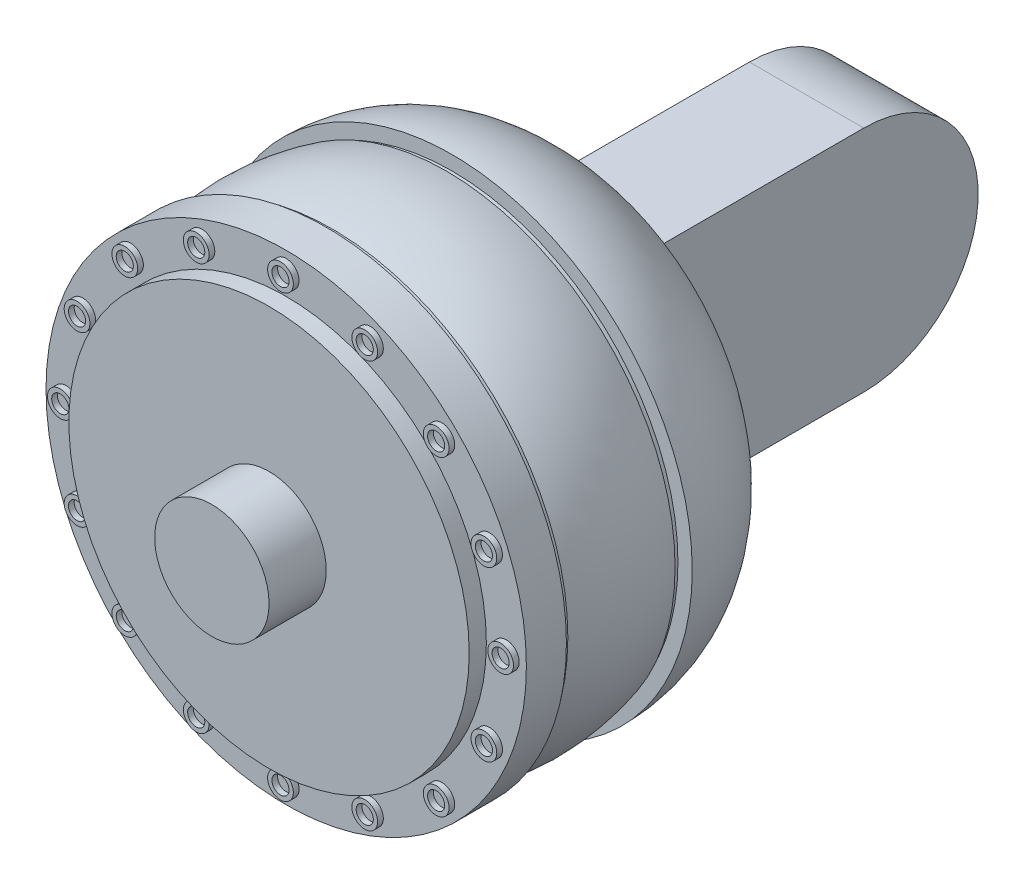
SolidWorks part; units mm, degrees
ref_plane "Front Plane" through (0, 0, 0) normal (0, 0, 1) x (1, 0, 0)
ref_plane "Top Plane" through (0, 0, 0) normal (0, 1, 0) x (1, 0, 0)
ref_plane "Right Plane" through (0, 0, 0) normal (1, 0, 0) x (0, 0, -1)
sketch "Sketch1" plane through (0, 0, 0) normal (0, 1, 0) x (1, 0, 0)
  line L0 (0, 0) -> (0, -20)
  line L1 (0, -20) -> (-42, -20)
  line L2 (-32, 0) -> (0, 0)
  arc A0 (-42, -20) -> (-32, 0) centre (-17, -20) cw
  dimension "D3" = 25
  dimension "D1" = 20
  dimension "D2" = 42
revolve "Revolve1" add sketch "Sketch1" angle 360 about L0
sketch "Sketch2" plane through (0, 0, 20) normal (0, 0, 1) x (1, 0, 0)
  circle A0 centre (0, 0) radius 39.5
  dimension "D1" = 79
extrude "Boss-Extrude1" add sketch "Sketch2" along normal blind 1
sketch "Sketch3" plane through (0, 0, 0) normal (0, 1, 0) x (1, 0, 0)
  line L0 (0, -21) -> (-40, -21)
  line L1 (-39.5, -21) -> (39.5, -21) construction
  line L2 (0, -21) -> (0, -41)
  line L3 (0, -41) -> (-40, -41)
  arc A1 (-40, -21) -> (-40, -41) centre (-4.377, -31) ccw
  dimension "D3" = 37
  dimension "D1" = 40
  dimension "D2" = 20
revolve "Revolve2" add sketch "Sketch3" angle 360 about L2
sketch "Sketch4" plane through (0, 0, 41) normal (0, 0, 1) x (1, 0, 0)
  circle A0 centre (0, 0) radius 41.25
  dimension "D1" = 82.5
extrude "Boss-Extrude2" add sketch "Sketch4" along normal blind 1
sketch "Sketch5" plane through (0, 0, 42) normal (0, 0, 1) x (1, 0, 0)
  circle A0 centre (0, 0) radius 42
  dimension "D1" = 84
extrude "Boss-Extrude3" add sketch "Sketch5" along normal blind 7
sketch "Sketch6" plane through (0, 0, 49) normal (0, 0, 1) x (1, 0, 0)
  circle A0 centre (0, 0) radius 35
  dimension "D1" = 70
extrude "Boss-Extrude4" add sketch "Sketch6" along normal blind 3
sketch "Sketch7" plane through (0, 0, 49) normal (0, 0, 1) x (1, 0, 0)
  circle A3 centre (38.5, 0) radius 2.25
  circle A4 centre (38.5, 0) radius 1.5
  dimension "D1" = 4.5
  dimension "D2" = 3
extrude "Boss-Extrude5" add sketch "Sketch7" along normal blind 1
pattern_circular "CirPattern1" count 16 over 360 about axis through (0, 0, 0) along (0, 0, 1) of "Boss-Extrude5"
sketch "Sketch8" plane through (0, 0, 0) normal (0, 0, -1) x (-1, 0, 0)
  line L1 (-10, 20) -> (10, 20)
  line L2 (-10, 20) -> (-10, -20)
  line L3 (-10, -20) -> (10, -20)
  line L4 (10, 20) -> (10, -20)
  line L5 (-10, 20) -> (10, -20) construction
  line L6 (-10, -20) -> (10, 20) construction
  point P0 (0, 0)
  dimension "D1" = 40
  dimension "D2" = 20
extrude "Boss-Extrude6" add sketch "Sketch8" along normal blind 42
sketch "Sketch9" plane through (-10, 0, 0) normal (-1, 0, 0) x (0, 0, 1)
  line L0 (-42, -20) -> (-42, 20) construction
  circle A0 centre (-42, 0) radius 20
extrude "Boss-Extrude7" add sketch "Sketch9" against normal up to surface (20 mm away) up to face at (10, 0, -21)
sketch "Sketch10" plane through (-10, 0, 0) normal (-1, 0, 0) x (0, 0, 1)
  circle A0 centre (-42, 0) radius 10
  dimension "D1" = 20
extrude "Boss-Extrude8" add sketch "Sketch10" along normal blind 10
sketch "Sketch11" plane through (0, 0, 52) normal (0, 0, 1) x (1, 0, 0)
  circle A0 centre (0, 0) radius 10
  dimension "D1" = 20
extrude "Boss-Extrude9" add sketch "Sketch11" along normal blind 10
